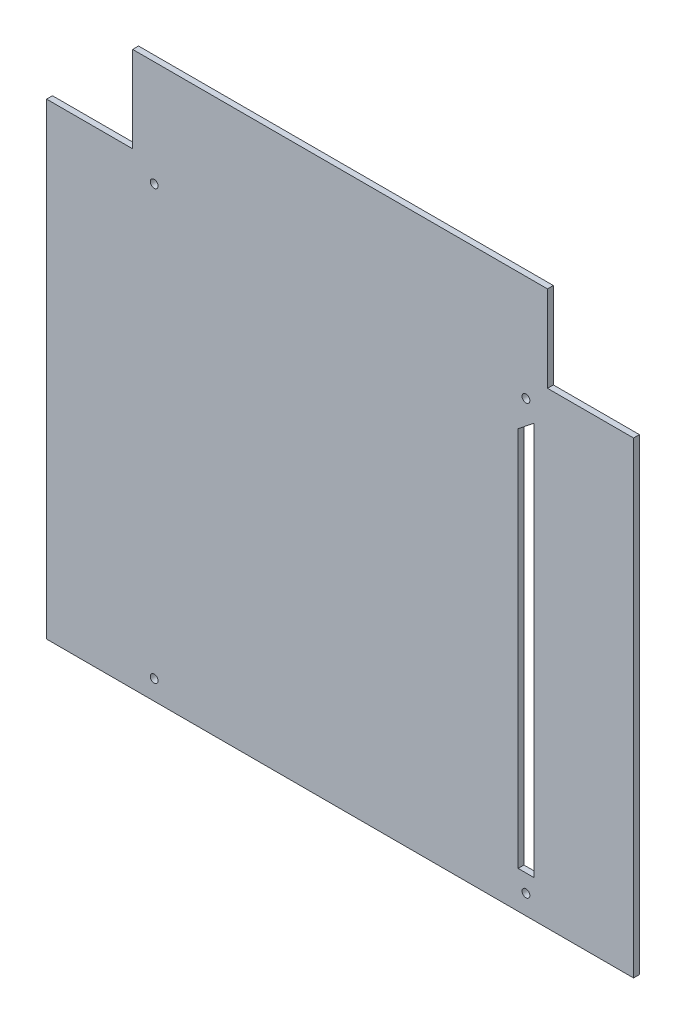
SolidWorks part; units mm, degrees
ref_plane "Front Plane" through (0, 0, 0) normal (0, 0, 1) x (1, 0, 0)
ref_plane "Top Plane" through (0, 0, 0) normal (0, 1, 0) x (1, 0, 0)
ref_plane "Right Plane" through (0, 0, 0) normal (1, 0, 0) x (0, 0, -1)
sketch "Sketch1" plane through (0, 0, 0) normal (0, 0, 1) x (1, 0, 0)
  line L0 (0, 0) -> (-206.9982, 0) construction
  line L1 (150, -119.5) -> (-150, -119.5)
  line L2 (150, -119.5) -> (150, 119.5)
  line L3 (150, 119.5) -> (-150, 119.5)
  line L4 (-150, -119.5) -> (-150, 119.5)
  line L5 (150, -119.5) -> (-150, 119.5) construction
  line L6 (150, 119.5) -> (-150, -119.5) construction
  line L7 (137.4477, -109.5) -> (-137.4477, -109.5) construction
  line L8 (137.4477, -109.5) -> (137.4477, 109.5) construction
  line L9 (137.4477, 109.5) -> (-137.4477, 109.5) construction
  line L10 (-137.4477, -109.5) -> (-137.4477, 109.5) construction
  line L11 (137.4477, -109.5) -> (-137.4477, 109.5) construction
  line L12 (137.4477, 109.5) -> (-137.4477, -109.5) construction
  line L13 (99, 100.5) -> (99, -100.5)
  line L14 (91, 94.1267) -> (91, -94.1267)
  line L15 (99, 100.5) -> (91, 94.1267)
  line L16 (99, -100.5) -> (91, -94.1267)
  line L17 (82, 112) -> (-82, 112)
  line L18 (95, 94.1267) -> (95, -94.1267) construction
  line L19 (-82, 112) -> (-75.7238, 107)
  line L20 (82, 112) -> (75.7238, 107)
  line L21 (137.4477, 112) -> (-137.4477, 112) construction
  line L22 (75.7238, 107) -> (-75.7238, 107)
  line L23 (99, -100.5) -> (91, -100.5)
  line L24 (91, -100.5) -> (91, -94.1267)
  line L26 (106, 119.5) -> (-106, 119.5)
  line L27 (106, 119.5) -> (106, 163.5)
  line L28 (106, 163.5) -> (-106, 163.5)
  line L29 (-106, 119.5) -> (-106, 163.5)
  circle A0 centre (-95, 109.5) radius 2
  circle A1 centre (95, 109.5) radius 2
  circle A2 centre (95, -109.5) radius 2
  circle A3 centre (-95, -109.5) radius 2
  point P0 (0, 0)
  point P5 (0, 0)
  dimension "D4" = 4
  dimension "D5" = 4
  dimension "D1" = 300
  dimension "D2" = 239
  dimension "D3" = 10
  dimension "D6" = 55
  dimension "D7" = 55
  dimension "D8" = 9
  dimension "D9" = 8
  dimension "D10" = 55
  dimension "D11" = 9
  dimension "D14" = 13
  dimension "D15" = 13
  dimension "D13" = 2.5
  dimension "D17" = 44
  dimension "D18" = 44
  dimension "D19" = 44
  dimension "D12" = 2.5
  dimension "D16" = 4
extrude "Boss-Extrude1" add sketch "Sketch1" along normal blind 3 contours L22 L20 L17 L19 | L4 L1 L2 L3 A2 A1 A0 L13 L16 L14 L15 L20 L22 L19 L17 A3 | L29 L3 L27 L28
